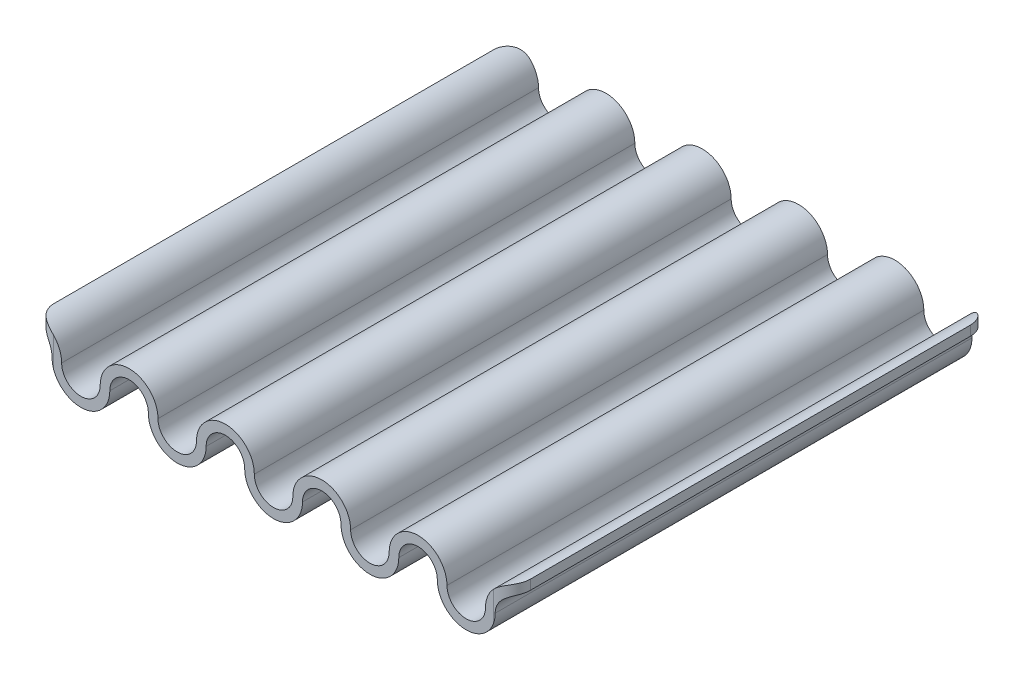
SolidWorks part; units mm, degrees
ref_plane "Front Plane" through (0, 0, 0) normal (0, 0, 1) x (1, 0, 0)
ref_plane "Top Plane" through (0, 0, 0) normal (0, 1, 0) x (1, 0, 0)
ref_plane "Right Plane" through (0, 0, 0) normal (1, 0, 0) x (0, 0, -1)
sketch "Sketch2" plane through (0, 0, 0) normal (0, 0, 1) x (1, 0, 0)
  line L14 (25.715, 6.2333) -> (25.715, 0) construction
  line L16 (51.43, 6.2333) -> (0, 6.2333)
  line L17 (51.43, 6.2333) -> (51.43, 0)
  line L18 (51.43, 0) -> (0, 0)
  line L19 (0, 6.2333) -> (0, 0)
  line L20 (51.43, 6.2333) -> (0, 0) construction
  line L21 (51.43, 0) -> (0, 6.2333) construction
  line L22 (25.715, 0) -> (25.715, 3.1167) construction
  line L23 (25.715, 3.1167) -> (0, 3.1167) construction
  line L24 (0, 3.1167) -> (0.5, 3.1167)
  line L25 (0, 6.2333) -> (-2.602, 6.2333)
  arc A43 (22.5983, 3.1167) -> (28.8317, 3.1167) centre (25.715, 3.1167) ccw
  arc A46 (23.6372, 3.1167) -> (27.7928, 3.1167) centre (25.715, 3.1167) ccw
  arc A51 (23.6372, 3.1167) -> (17.4039, 3.1167) centre (20.5206, 3.1167) ccw
  arc A52 (22.5983, 3.1167) -> (18.4428, 3.1167) centre (20.5206, 3.1167) ccw
  arc A53 (12.2094, 3.1167) -> (18.4428, 3.1167) centre (15.3261, 3.1167) ccw
  arc A54 (13.2483, 3.1167) -> (17.4039, 3.1167) centre (15.3261, 3.1167) ccw
  arc A56 (12.2094, 3.1167) -> (8.0539, 3.1167) centre (10.1317, 3.1167) ccw
  arc A57 (1.8206, 3.1167) -> (8.0539, 3.1167) centre (4.9372, 3.1167) ccw
  arc A58 (2.8594, 3.1167) -> (7.015, 3.1167) centre (4.9372, 3.1167) ccw
  arc A59 (1.8206, 3.1167) -> (0, 5.1785) centre (-0.2572, 3.1167) ccw
  arc A60 (2.8594, 3.1167) -> (-0.2572, 6.2333) centre (-0.2572, 3.1167) ccw
  arc A61 (49.6094, 3.1167) -> (51.43, 5.1785) centre (51.6872, 3.1167) cw
  arc A62 (13.2483, 3.1167) -> (7.015, 3.1167) centre (10.1317, 3.1167) ccw
  arc A63 (48.5706, 3.1167) -> (51.6872, 6.2333) centre (51.6872, 3.1167) cw
  arc A64 (48.5706, 3.1167) -> (44.415, 3.1167) centre (46.4928, 3.1167) cw
  arc A65 (49.6094, 3.1167) -> (43.3761, 3.1167) centre (46.4928, 3.1167) cw
  arc A66 (39.2206, 3.1167) -> (43.3761, 3.1167) centre (41.2983, 3.1167) cw
  arc A67 (38.1817, 3.1167) -> (44.415, 3.1167) centre (41.2983, 3.1167) cw
  arc A68 (38.1817, 3.1167) -> (34.0261, 3.1167) centre (36.1039, 3.1167) cw
  arc A69 (39.2206, 3.1167) -> (32.9872, 3.1167) centre (36.1039, 3.1167) cw
  arc A70 (28.8317, 3.1167) -> (32.9872, 3.1167) centre (30.9094, 3.1167) cw
  arc A71 (27.7928, 3.1167) -> (34.0261, 3.1167) centre (30.9094, 3.1167) cw
  point P0 (25.715, 3.1167)
  point P2 (25.715, 3.1167)
  point P40 (0, 3.1167)
  dimension "D3" = 2.0778
  dimension "D4" = 2.0778
  dimension "D5" = 2.0778
  dimension "D1" = 51.43
  dimension "D2" = 6.2333
extrude "Boss-Extrude3" add sketch "Sketch2" along normal blind 51.43 contours A71 A46 A51 A54 A62 A58 A60 L19 A59 A57 A56 A53 A52 A43 A70 A69 A66 A65 A61 L17 A63 A64 A67 A68
ref_plane "Plane1" through (0, 6.2333, 0) normal (0, 1, 0) x (1, 0, 0)
sketch "Sketch3" plane through (0, 6.2333, 0) normal (0, 1, 0) x (1, 0, 0)
  line L0 (51.43, -49.43) -> (51.43, -51.43)
  line L5 (51.43, 0) -> (49.43, 0)
  line L6 (51.43, 0) -> (51.43, -2)
  line L7 (51.43, -51.43) -> (49.43, -51.43)
  line L8 (0, 0) -> (0, -2)
  line L9 (51.43, 0) -> (0, -51.43) construction
  line L10 (51.43, -51.43) -> (0, 0) construction
  line L11 (2, 0) -> (0, 0)
  line L12 (0, -49.43) -> (0, -51.43)
  line L13 (2, -51.43) -> (0, -51.43)
  arc A0 (2, 0) -> (0, -2) centre (2, -2) ccw
  arc A1 (0, -49.43) -> (2, -51.43) centre (2, -49.43) ccw
  arc A2 (49.43, -51.43) -> (51.43, -49.43) centre (49.43, -49.43) ccw
  arc A3 (49.43, 0) -> (51.43, -2) centre (49.43, -2) cw
  point P12 (0, -51.43)
  point P17 (51.43, 0)
  point P18 (25.715, -25.715)
  dimension "D1" = 2
extrude "Cut-Extrude1" cut sketch "Sketch3" against normal blind 10
